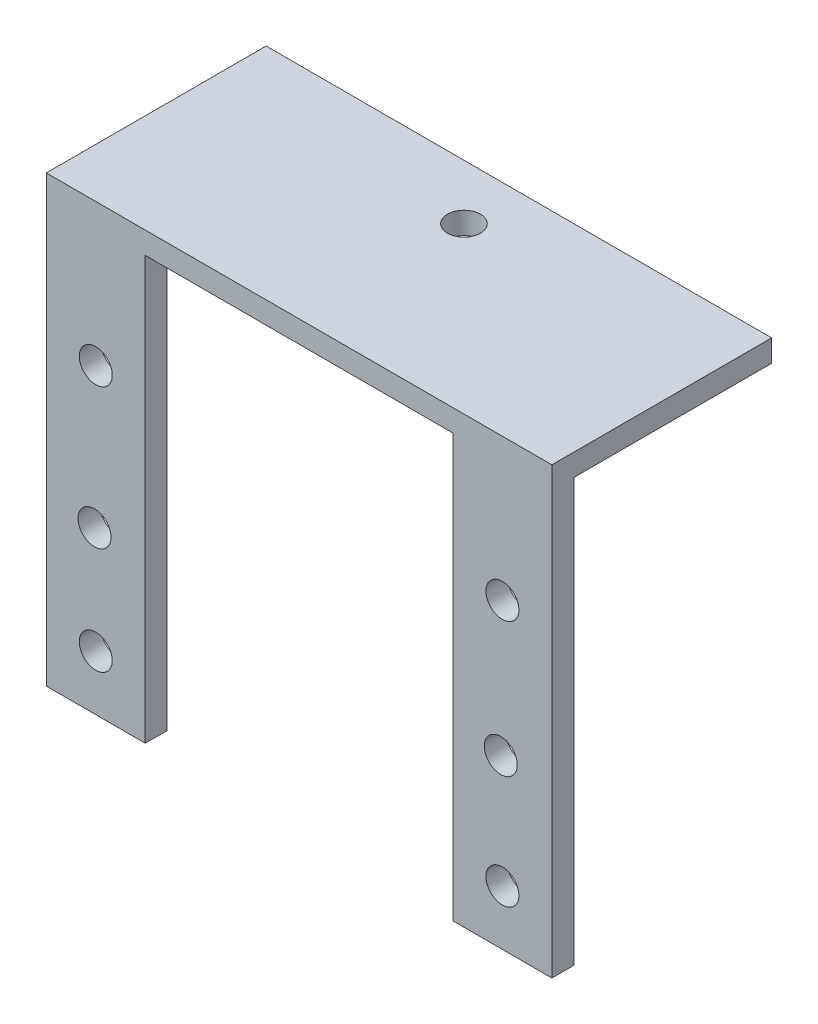
SolidWorks part; units mm, degrees
ref_plane "Front Plane" through (0, 0, 0) normal (0, 0, 1) x (1, 0, 0)
ref_plane "Top Plane" through (0, 0, 0) normal (0, 1, 0) x (1, 0, 0)
ref_plane "Right Plane" through (0, 0, 0) normal (1, 0, 0) x (0, 0, -1)
ref_plane "Plane1" through (0, 0, 0) normal (0, 0, 1) x (1, 0, 0)
ref_plane "Plane2" through (0, 4, 0) normal (0, 1, 0) x (1, 0, 0)
ref_plane "Plane3" through (0, 0, 0) normal (1, 0, 0) x (0, 0, -1)
sketch "Sketch3" plane through (0, 0, 0) normal (0, 0, 1) x (1, 0, 0)
  line L1 (-16.5158, -34.4383) -> (-25.5158, -34.4383)
  line L2 (-16.5158, -34.4383) -> (-16.5158, 5.5617)
  line L3 (-16.5158, 5.5617) -> (-25.5158, 5.5617)
  line L4 (-25.5158, -34.4383) -> (-25.5158, 5.5617)
  line L5 (20.4842, -34.4383) -> (11.4842, -34.4383)
  line L6 (20.4842, -34.4383) -> (20.4842, 5.5617)
  line L7 (20.4842, 5.5617) -> (11.4842, 5.5617)
  line L8 (11.4842, -34.4383) -> (11.4842, 5.5617)
  circle A0 centre (15.9842, -29.4383) radius 1.5
  circle A1 centre (-21.0158, -29.4383) radius 1.5
  circle A2 centre (-21.0158, -6.9383) radius 1.5
  circle A3 centre (15.9842, -6.9383) radius 1.5
  dimension "D4" = 3
  dimension "D5" = 4.5
  dimension "D6" = 5
  dimension "D7" = 22.5
  dimension "D8" = 22.5
  dimension "D9" = 5
  dimension "D1" = 40
  dimension "D2" = 9
  dimension "D3" = 46
  dimension "4.5" = 4.5
  dimension "D10" = 37
extrude "Boss-Extrude5" add sketch "Sketch3" along normal blind 2
sketch "Sketch5" plane through (0, 4, 0) normal (0, 1, 0) x (1, 0, 0)
  line L1 (-25.5158, -2) -> (20.4842, -2)
  line L2 (-25.5158, -2) -> (-25.5158, 18)
  line L3 (-25.5158, 18) -> (20.4842, 18)
  line L4 (20.4842, -2) -> (20.4842, 18)
  circle A0 centre (-2.5158, 13) radius 1.5
  dimension "D3" = 3
  dimension "D1" = 46
  dimension "D2" = 20
  dimension "D4" = 5
  dimension "D5" = 23
extrude "Boss-Extrude7" add sketch "Sketch5" along normal blind 2
sketch "Sketch6" plane through (0, 0, 2) normal (0, 0, 1) x (1, 0, 0)
  circle A0 centre (15.8341, -19.2316) radius 1.5
  circle A1 centre (15.9842, -29.4383) radius 1.5 construction
extrude "Cut-Extrude1" cut sketch "Sketch6" against normal blind 10
sketch "Sketch7" plane through (0, 0, 2) normal (0, 0, 1) x (1, 0, 0)
  circle A0 centre (-21.1275, -19.7709) radius 1.5
  circle A1 centre (-21.0158, -29.4383) radius 1.5 construction
extrude "Cut-Extrude2" cut sketch "Sketch7" against normal blind 10
